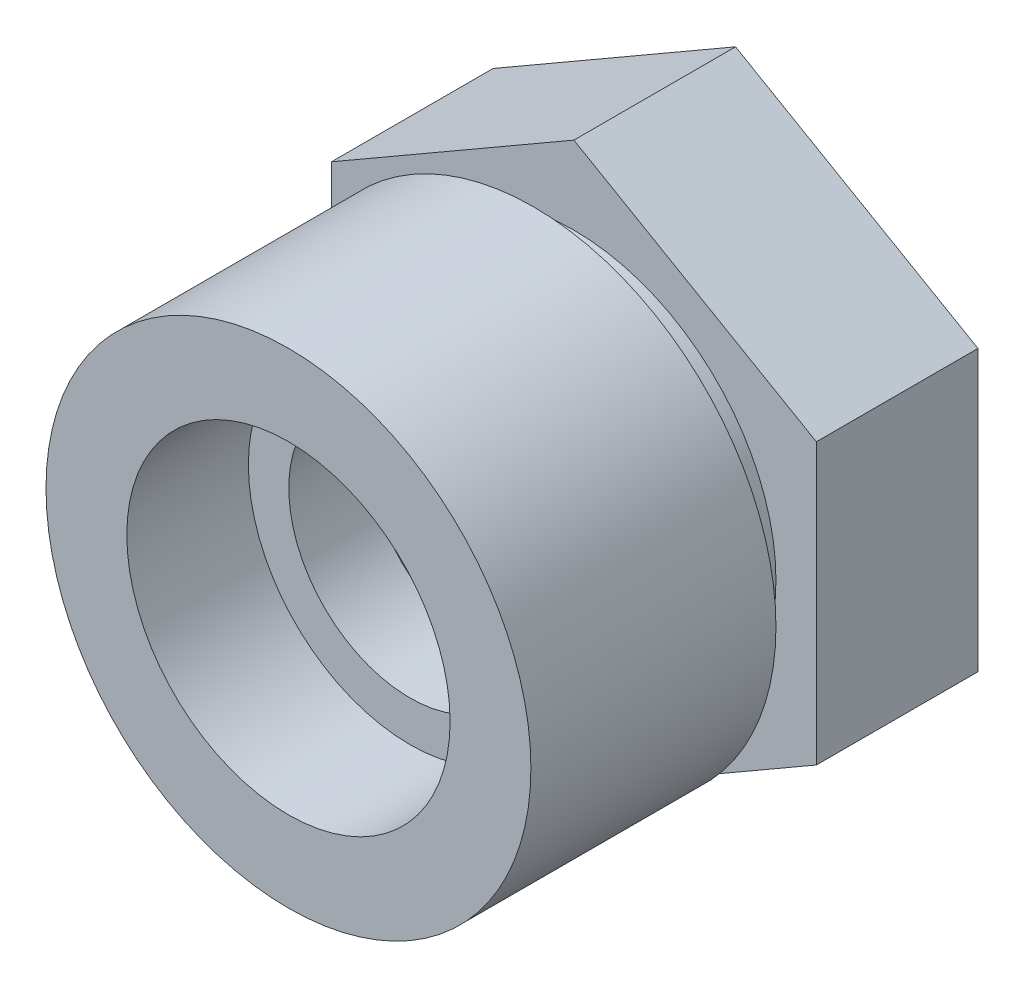
SolidWorks part; units mm, degrees
ref_plane "Front Plane" through (0, 0, 0) normal (0, 0, 1) x (1, 0, 0)
ref_plane "Top Plane" through (0, 0, 0) normal (0, 1, 0) x (1, 0, 0)
ref_plane "Right Plane" through (0, 0, 0) normal (1, 0, 0) x (0, 0, -1)
sketch "Sketch1" plane through (0, 0, 0) normal (0, 0, 1) x (1, 0, 0)
  line L1 (0, -10.9985) -> (9.525, -5.4993)
  line L2 (9.525, -5.4993) -> (9.525, 5.4993)
  line L3 (9.525, 5.4993) -> (0, 10.9985)
  line L4 (0, 10.9985) -> (-9.525, 5.4993)
  line L5 (-9.525, 5.4993) -> (-9.525, -5.4993)
  line L6 (-9.525, -5.4993) -> (0, -10.9985)
  circle A0 centre (0, 0) radius 9.525 construction
  dimension "D1" = 19.05
extrude "Boss-Extrude1" add sketch "Sketch1" against normal blind 6.35
sketch "Sketch2" plane through (0, 0, 0) normal (0, 0, 1) x (1, 0, 0)
  circle A0 centre (0, 0) radius 7.9375
  dimension "D1" = 15.875
extrude "Boss-Extrude3" add sketch "Sketch2" along normal blind 1.5875 separate body
sketch "Sketch7" plane through (0, 0, 1.5875) normal (0, 0, 1) x (1, 0, 0)
  circle A0 centre (0, 0) radius 9.525
  dimension "D1" = 19.05
extrude "Boss-Extrude4" add sketch "Sketch7" along normal blind 9.6266
cosmetic thread "Cosmetic Thread2" parameters "D1"=9.6266, "D2"=14.1961
hole_wizard "#10-32 Tapped Hole2" positions "Sketch11" profile "Sketch10" tap size "#10-32" standard "ANSI Inch" end condition through all
sketch "Sketch11" plane through (0, 0, -6.35) normal (0, 0, -1) x (-1, 0, 0)
  point P0 (0, 0)
sketch "Sketch10" plane through (0, 0, -6.35) normal (1, 0, 0) x (0, 1, 0)
  line L0 (0, 0) -> (0, 17.5641)
  line L1 (0, 17.5641) -> (2.0193, 17.5641)
  line L2 (2.0193, 17.5641) -> (2.0193, 0)
  line L5 (2.0193, 0) -> (0, 0)
  line L11 (0, -6.35) -> (0, 107.95) construction
  dimension "Thru Tap Drill Dia." = 4.0386
  dimension "Thru Tap Drill Depth" = 17.5641
cosmetic thread "Hole Thread2" parameters "D2"=4.826
sketch "Sketch12" plane through (0, 0, 11.2141) normal (0, 0, 1) x (1, 0, 0)
  circle A0 centre (0, 0) radius 6.35
  dimension "D1" = 12.7
extrude "Cut-Extrude5" cut sketch "Sketch12" against normal blind 4.7752
sketch "Sketch13" plane through (0, 0, 6.4389) normal (0, 0, 1) x (1, 0, 0)
  circle A0 centre (0, 0) radius 4.7625
  dimension "D1" = 9.525
extrude "Cut-Extrude6" cut sketch "Sketch13" against normal blind 3.048
